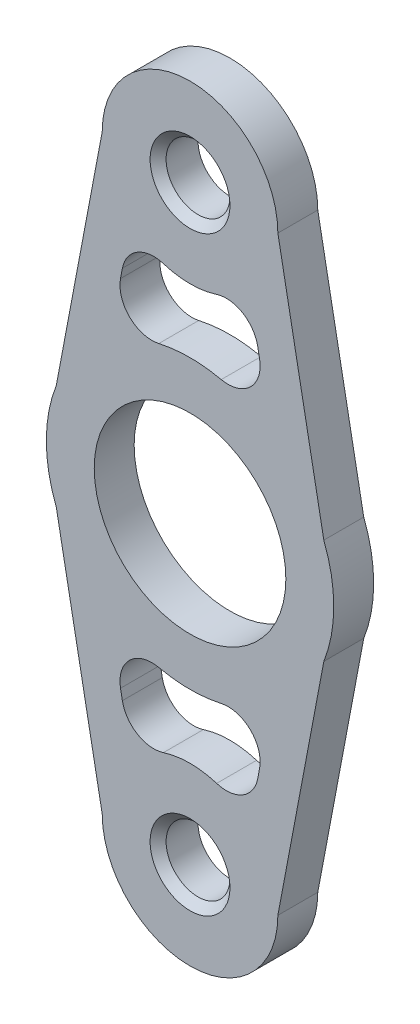
SolidWorks part; units mm, degrees
ref_plane "Front Plane" through (0, 0, 0) normal (1, 0, 0) x (0, 1, 0)
ref_plane "Top Plane" through (0, 0, 0) normal (0, 0, 1) x (0, 1, 0)
ref_plane "Right Plane" through (0, 0, 0) normal (0, 1, 0) x (-1, 0, 0)
sketch "Sketch1" plane through (0, 0, 0) normal (0, 0, 1) x (0, 1, 0)
  line L0 (-63.7423, 0) -> (18, 0) construction
  line L1 (6.5755, 16.756) -> (37, 11)
  line L2 (6.5755, -16.756) -> (37, -11)
  line L3 (-1.2528, 13.1483) -> (39.2408, 5.4874) construction
  line L4 (26, 0) -> (68.8158, 0) construction
  line L5 (23.4486, 8.4751) -> (22.2186, 8.7078)
  line L6 (23.4486, -8.4751) -> (22.2186, -8.7078)
  line L7 (0, 30) -> (0, -30) construction
  line L8 (-23.4486, -8.4751) -> (-22.2186, -8.7078)
  line L9 (-23.4486, 8.4751) -> (-22.2186, 8.7078)
  line L10 (-6.5755, 16.756) -> (-37, 11)
  line L11 (-6.5755, -16.756) -> (-37, -11)
  circle A0 centre (0, 0) radius 12
  arc A1 (6.5755, 16.756) -> (-6.5755, 16.756) centre (0, 0) ccw
  circle A2 centre (37, 0) radius 4
  arc A3 (26.5171, 3.3328) -> (26.5171, -3.3328) centre (37, 0) ccw
  arc A4 (26.5171, 3.3328) -> (23.4486, 8.4751) centre (22.7051, 4.5448) ccw
  arc A5 (22.2186, 8.7078) -> (17.5704, 3.9089) centre (21.475, 4.7775) ccw
  arc A6 (22.2186, -8.7078) -> (17.5704, -3.9089) centre (21.475, -4.7775) cw
  arc A7 (26.5171, -3.3328) -> (23.4486, -8.4751) centre (22.7051, -4.5448) cw
  arc A8 (-22.2186, -8.7078) -> (-17.5704, -3.9089) centre (-21.475, -4.7775) ccw
  arc A9 (-26.5171, -3.3328) -> (-23.4486, -8.4751) centre (-22.7051, -4.5448) ccw
  arc A10 (-26.5171, 3.3328) -> (-23.4486, 8.4751) centre (-22.7051, 4.5448) cw
  arc A11 (-22.2186, 8.7078) -> (-17.5704, 3.9089) centre (-21.475, 4.7775) cw
  circle A12 centre (-37, 0) radius 4
  arc A13 (-26.5171, 3.3328) -> (-26.5171, -3.3328) centre (-37, 0) cw
  arc A14 (17.5704, -3.9089) -> (17.5704, 3.9089) centre (0, 0) ccw
  arc A15 (-6.5755, -16.756) -> (6.5755, -16.756) centre (0, 0) ccw
  arc A16 (-17.5704, 3.9089) -> (-17.5704, -3.9089) centre (0, 0) ccw
  arc A17 (-37, -11) -> (-37, 11) centre (-37, 0) cw
  arc A18 (37, -11) -> (37, 11) centre (37, 0) ccw
  point P31 (0, 0)
  point P32 (0, 0)
  dimension "D1" = 24
  dimension "D2" = 36
  dimension "D4" = 8
  dimension "D5" = 22
  dimension "D7" = 4
  dimension "D3" = 37
  dimension "D6" = 5
extrude "Boss-Extrude1" add sketch "Sketch1" along normal blind 5
chamfer "Chamfer1" distance 1 angle 45 2 edges at (-4, -37, 5) (4, 37, 5)
